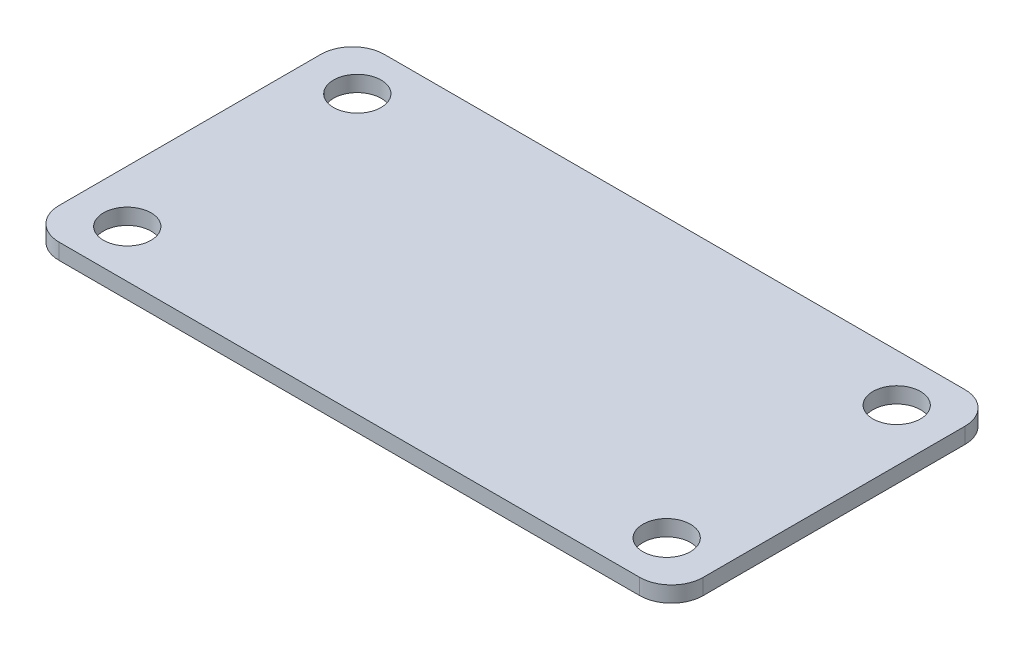
SolidWorks part; units mm, degrees
ref_plane "Спереди" through (0, 0, 0) normal (0, 0, 1) x (1, 0, 0)
ref_plane "Сверху" through (0, 0, 0) normal (0, 1, 0) x (1, 0, 0)
ref_plane "Справа" through (0, 0, 0) normal (1, 0, 0) x (0, 0, -1)
sketch "Эскиз1" plane through (0, 0, 0) normal (0, 1, 0) x (1, 0, 0)
  line L0 (-17, -7.25) -> (-17, 7.25) construction
  line L1 (-20.3, 10.25) -> (20.3, 10.25)
  line L2 (-20.3, 10.25) -> (-20.3, -10.25)
  line L3 (-20.3, -10.25) -> (20.3, -10.25)
  line L4 (20.3, 10.25) -> (20.3, -10.25)
  line L5 (-17, 7.25) -> (17, 7.25) construction
  circle A0 centre (-17, 7.25) radius 1.5
  circle A1 centre (-17, -7.25) radius 1.5
  circle A2 centre (17, -7.25) radius 1.5
  circle A3 centre (17, 7.25) radius 1.5
  point P4 (0, 10.25)
  point P6 (-20.3, 0)
  point P15 (0, 7.25)
  point P16 (-17, 0)
  point P17 (0, 0)
  point P18 (0, 0)
  point P19 (0, 0)
  dimension "D3" = 3
  dimension "D1" = 40.6
  dimension "D2" = 20.5
  dimension "D4" = 14.5
  dimension "D5" = 34
extrude "Бобышка-Вытянуть1" add sketch "Эскиз1" along normal blind 1
fillet "Скругление1" radius 2 4 edges at (-20.3, 0.5, -10.25) (20.3, 0.5, -10.25) (20.3, 0.5, 10.25) (-20.3, 0.5, 10.25)
